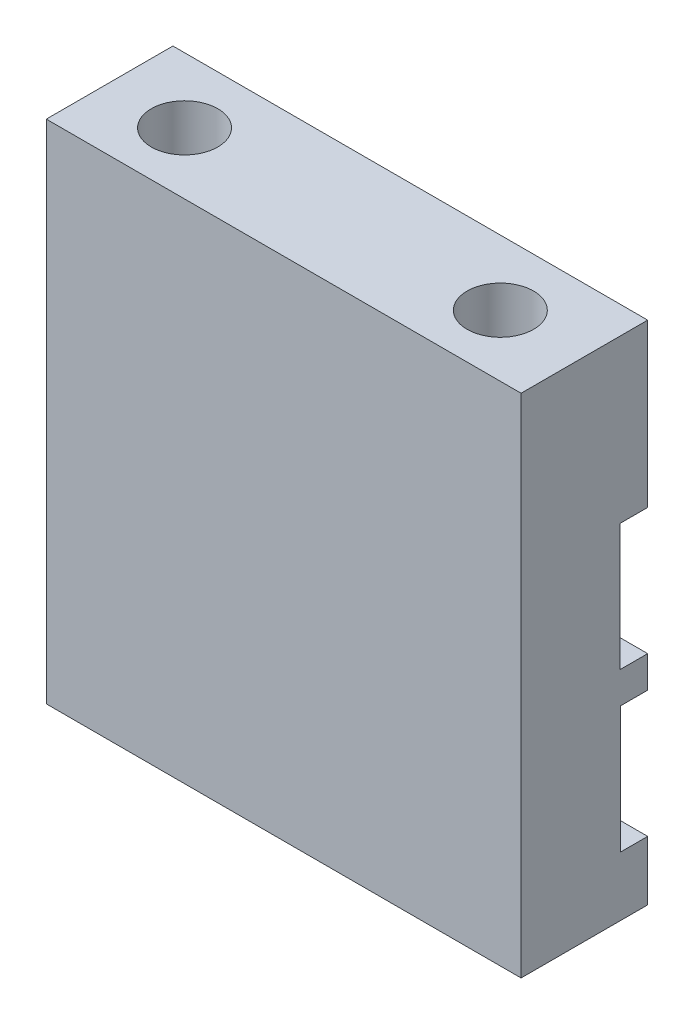
SolidWorks part; units mm, degrees
ref_plane "Front Plane" through (0, 0, 0) normal (0, 0, 1) x (1, 0, 0)
ref_plane "Top Plane" through (0, 0, 0) normal (0, 1, 0) x (1, 0, 0)
ref_plane "Right Plane" through (0, 0, 0) normal (1, 0, 0) x (0, 0, -1)
sketch "Sketch1" plane through (0, 0, 0) normal (0, 0, 1) x (1, 0, 0)
  line L1 (-15, 16) -> (15, 16)
  line L2 (-15, 16) -> (-15, -16)
  line L3 (-15, -16) -> (15, -16)
  line L4 (15, 16) -> (15, -16)
  line L5 (-15, 16) -> (15, -16) construction
  line L6 (-15, -16) -> (15, 16) construction
  point P0 (0, 0)
  dimension "D1" = 32
  dimension "D2" = 30
extrude "Boss-Extrude1" add sketch "Sketch1" along normal blind 8 and the other way blind 0.001
sketch "Sketch3" plane through (-15, 0, 0) normal (-1, 0, 0) x (0, 0, 1)
  line L0 (-0.001, 16) -> (-0.001, -16) construction
  line L1 (-0.001, 5.75) -> (1.749, 5.75)
  line L2 (-0.001, 5.75) -> (-0.001, -2.25)
  line L3 (-0.001, -2.25) -> (1.749, -2.25)
  line L4 (1.749, 5.75) -> (1.749, -2.25)
  line L6 (-0.001, -4.25) -> (1.7155, -4.25)
  line L7 (-0.001, -4.25) -> (-0.001, -12.25)
  line L8 (-0.001, -12.25) -> (1.7155, -12.25)
  line L9 (1.7155, -4.25) -> (1.7155, -12.25)
  dimension "D1" = 8
  dimension "D2" = 1.75
  dimension "D3" = 21.75
  dimension "D4" = 8
  dimension "D5" = 18
extrude "Cut-Extrude1" cut sketch "Sketch3" against normal through all
sketch "Sketch4" plane through (0, 16, 0) normal (0, 1, 0) x (1, 0, 0)
  circle A0 centre (-10.1532, -4.1109) radius 2.1
  circle A1 centre (9.8008, -4.1109) radius 2.1
  point P4 (0, 0)
  point P5 (-10.1532, -3.0312)
  point P6 (-10.1532, -4.1109)
  point P7 (0, 0)
  point P8 (9.8008, -4.1109)
  dimension "D1" = 4.2
extrude "Cut-Extrude2" cut sketch "Sketch4" against normal blind 6
